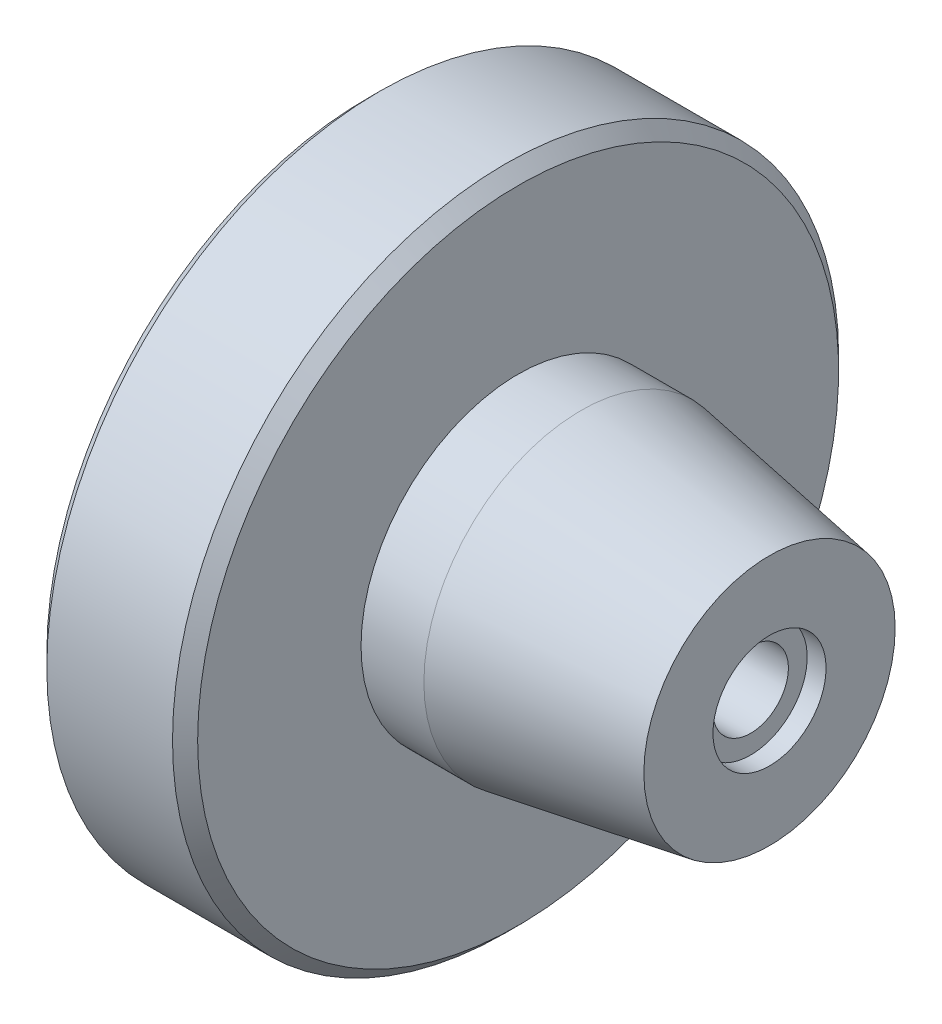
SolidWorks part; units mm, degrees
ref_plane "前视基准面" through (0, 0, 0) normal (0, 0, 1) x (1, 0, 0)
ref_plane "上视基准面" through (0, 0, 0) normal (0, 1, 0) x (1, 0, 0)
ref_plane "右视基准面" through (0, 0, 0) normal (1, 0, 0) x (0, 0, -1)
sketch "草图1" plane through (0, 0, 0) normal (0, 0, 1) x (1, 0, 0)
  line L0 (0, 11.5) -> (1, 12.5)
  line L1 (1, 12.5) -> (8, 12.5)
  line L2 (8, 12.5) -> (8, 25.5)
  line L3 (8, 25.5) -> (9, 26.5)
  line L4 (9, 26.5) -> (19, 26.5)
  line L5 (19, 26.5) -> (20, 25.5)
  line L6 (20, 25.5) -> (20, 12.5)
  line L7 (20, 12.5) -> (25, 12.5)
  line L8 (25, 12.5) -> (40, 10)
  line L9 (40, 10) -> (40, 4.5)
  line L10 (40, 4.5) -> (38.5, 4.5)
  line L11 (38.5, 4.5) -> (38.5, 3)
  line L12 (38.5, 3) -> (1.5, 3)
  line L13 (1.5, 3) -> (1.5, 4.5)
  line L14 (1.5, 4.5) -> (0, 4.5)
  line L15 (0, 4.5) -> (0, 11.5)
  line L16 (0, 0) -> (40, 0) construction
revolve "旋转1" add sketch "草图1" angle 360 about L16
sketch "草图2" plane through (0, 0, 0) normal (1, 0, 0) x (0, 0, -1)
  circle A0 centre (19, 0) radius 3.5
  circle A1 centre (-9.5, 16.4545) radius 3.5
  circle A2 centre (-9.5, -16.4545) radius 3.5
